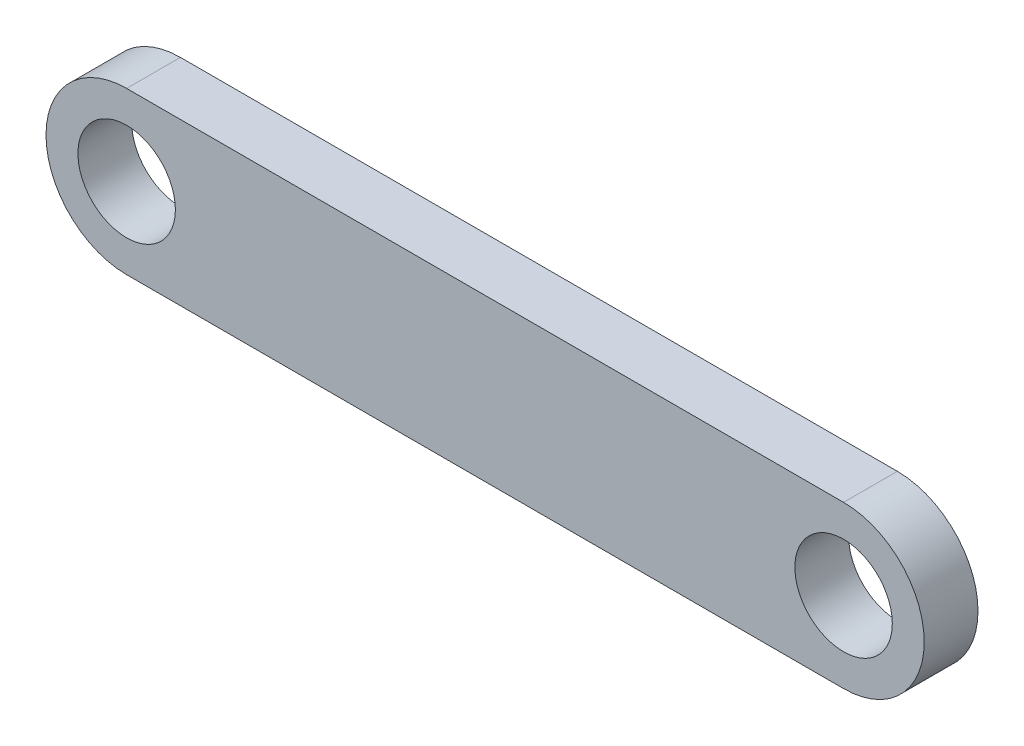
SolidWorks part; units mm, degrees
ref_plane "Front Plane" through (0, 0, 0) normal (0, 0, 1) x (1, 0, 0)
ref_plane "Top Plane" through (0, 0, 0) normal (0, 1, 0) x (1, 0, 0)
ref_plane "Right Plane" through (0, 0, 0) normal (1, 0, 0) x (0, 0, -1)
sketch "Sketch1" plane through (0, 0, 0) normal (0, 0, 1) x (1, 0, 0)
  line L0 (-27.2747, 0) -> (88.8406, 0) construction
  line L1 (0, 7.62) -> (67.7333, 7.62)
  line L2 (0, -7.62) -> (67.7333, -7.62)
  circle A0 centre (0, 0) radius 4.6037
  circle A1 centre (67.7333, 0) radius 4.6038
  arc A2 (0, 7.62) -> (0, -7.62) centre (0, 0) ccw
  arc A3 (67.7333, -7.62) -> (67.7333, 7.62) centre (67.7333, 0) ccw
  dimension "D1" = 9.2075
  dimension "D2" = 9.2075
  dimension "D4" = 15.24
  dimension "D5" = 15.24
  dimension "D3" = 67.7333
extrude "Boss-Extrude1" add sketch "Sketch1" along normal blind 5.08
